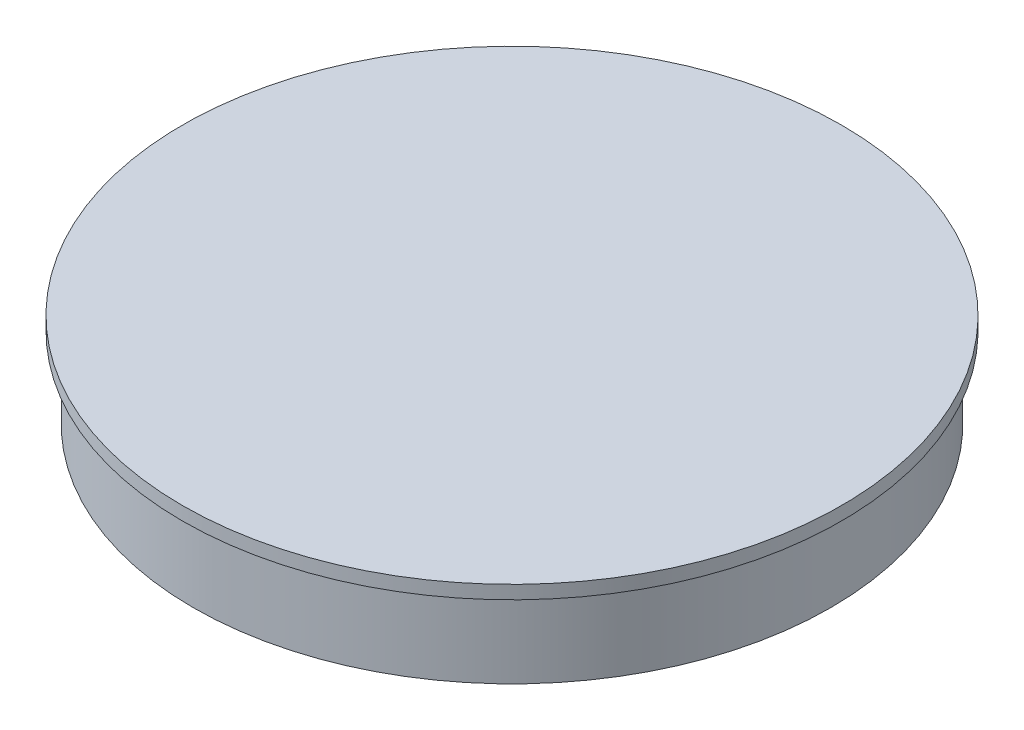
SolidWorks part; units mm, degrees
ref_plane "Front Plane" through (0, 0, 0) normal (0, 0, 1) x (1, 0, 0)
ref_plane "Top Plane" through (0, 0, 0) normal (0, 1, 0) x (1, 0, 0)
ref_plane "Right Plane" through (0, 0, 0) normal (1, 0, 0) x (0, 0, -1)
sketch "Sketch1" plane through (0, 0, 0) normal (0, 1, 0) x (1, 0, 0)
  circle A0 centre (0, 0) radius 35.7
  circle A1 centre (0, 0) radius 34.7
  dimension "D1" = 71.4
  dimension "D2" = 1
extrude "Boss-Extrude1" add sketch "Sketch1" along normal blind 9
sketch "Sketch2" plane through (0, 9, 0) normal (0, 1, 0) x (1, 0, 0)
  circle A0 centre (0, 0) radius 36.9
  dimension "D1" = 73.8
extrude "Boss-Extrude2" add sketch "Sketch2" along normal blind 1.5
